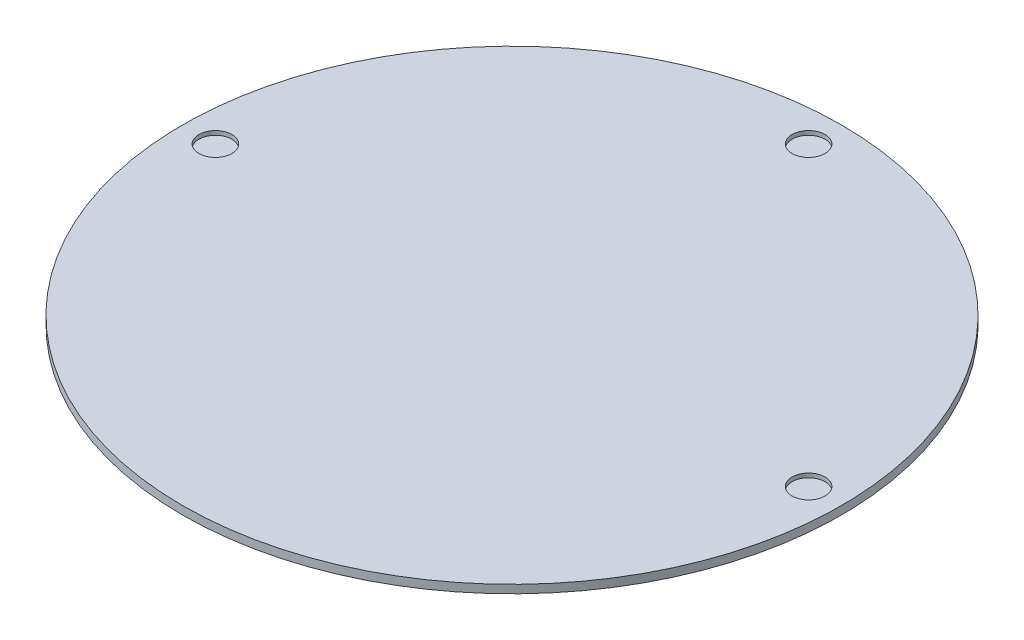
SolidWorks part; units mm, degrees
ref_plane "Front Plane" through (0, 0, 0) normal (0, 0, 1) x (1, 0, 0)
ref_plane "Top Plane" through (0, 0, 0) normal (0, 1, 0) x (1, 0, 0)
ref_plane "Right Plane" through (0, 0, 0) normal (1, 0, 0) x (0, 0, -1)
sketch "Sketch1" plane through (0, 0, 0) normal (0, 1, 0) x (1, 0, 0)
  circle A0 centre (0, 0) radius 400
extrude "Boss-Extrude1" add sketch "Sketch1" along normal blind 10
sketch "Sketch2" plane through (0, 10, 0) normal (0, 1, 0) x (1, 0, 0)
  line L0 (0, 0) -> (360, 0)
  line L1 (0, 0) -> (-360, 0)
  line L2 (0, 0) -> (0, 360)
  circle A0 centre (360, 0) radius 20
  circle A1 centre (-360, 0) radius 20
  circle A2 centre (0, 360) radius 20
extrude "Cut-Extrude2" cut sketch "Sketch2" against normal blind 5
